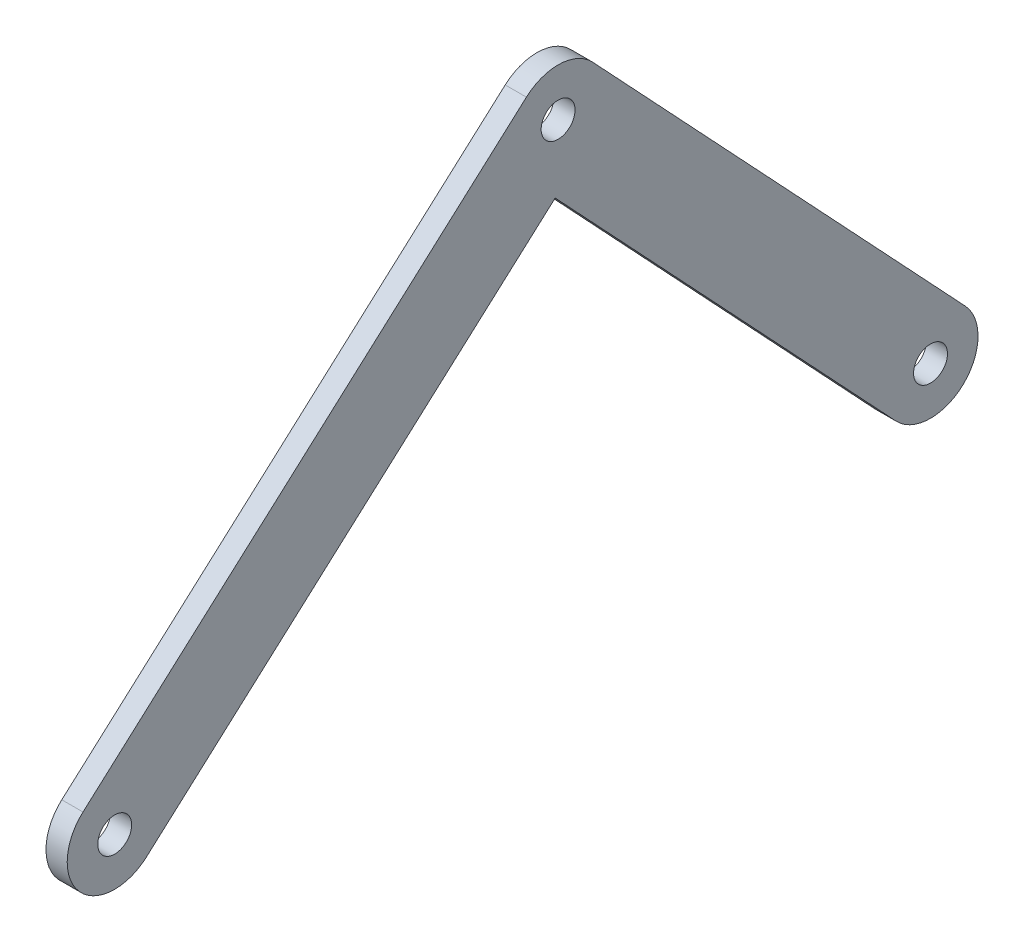
SolidWorks part; units mm, degrees
ref_plane "Front Plane" through (0, 0, 0) normal (0, 0, 1) x (1, 0, 0)
ref_plane "Top Plane" through (0, 0, 0) normal (0, 1, 0) x (1, 0, 0)
ref_plane "Right Plane" through (0, 0, 0) normal (1, 0, 0) x (0, 0, -1)
sketch "Sketch2" plane through (0, 0, 0) normal (1, 0, 0) x (0, 0, -1)
  line L0 (0, 0) -> (55.7786, -59.5123) construction
  line L1 (5.1891, 4.8635) -> (60.9677, -54.6488)
  line L2 (-5.1891, -4.8635) -> (50.5895, -64.3759)
  line L3 (0, 0) -> (-66.4074, -59.5123) construction
  line L4 (4.7465, -5.2964) -> (-61.6609, -64.8087)
  line L5 (-4.7465, 5.2964) -> (-71.1538, -54.216)
  arc A0 (5.1891, 4.8635) -> (-5.1891, -4.8635) centre (0, 0) ccw
  arc A1 (50.5895, -64.3759) -> (60.9677, -54.6488) centre (55.7786, -59.5123) ccw
  arc A2 (4.7465, -5.2964) -> (-4.7465, 5.2964) centre (0, 0) ccw
  arc A3 (-71.1538, -54.216) -> (-61.6609, -64.8087) centre (-66.4074, -59.5123) ccw
  point P3 (27.8893, -29.7562)
  point P8 (-33.2037, -29.7562)
  point P15 (0, 0)
  point P16 (-42.4534, -61.3016)
  point P17 (48.0919, -62.3364)
  point P18 (-51.0929, -62.8659)
  point P19 (-138.8589, -59.6474)
  point P20 (0, 0)
  point P21 (0, 0)
  point P22 (-48.502, -63.1862)
  point P23 (-261.3008, -59.5123)
  point P24 (-58.8824, -68.3764)
  point P25 (-146.6998, -59.5123)
  point P26 (-66.4074, -62.9271)
extrude "Boss-Extrude1" add sketch "Sketch2" along normal blind 3.175 contours A2 L4 L2 A1 L1 | L5 A3 L4 L2 A0 | L4 A2 A0 L2
sketch "Sketch3" plane through (3.175, 0, 0) normal (1, 0, 0) x (0, 0, -1)
  circle A0 centre (0, 0) radius 2.54
  circle A1 centre (-66.4074, -59.5123) radius 2.54
  circle A2 centre (55.7786, -59.5123) radius 2.54
extrude "Cut-Extrude1" cut sketch "Sketch3" against normal through all
